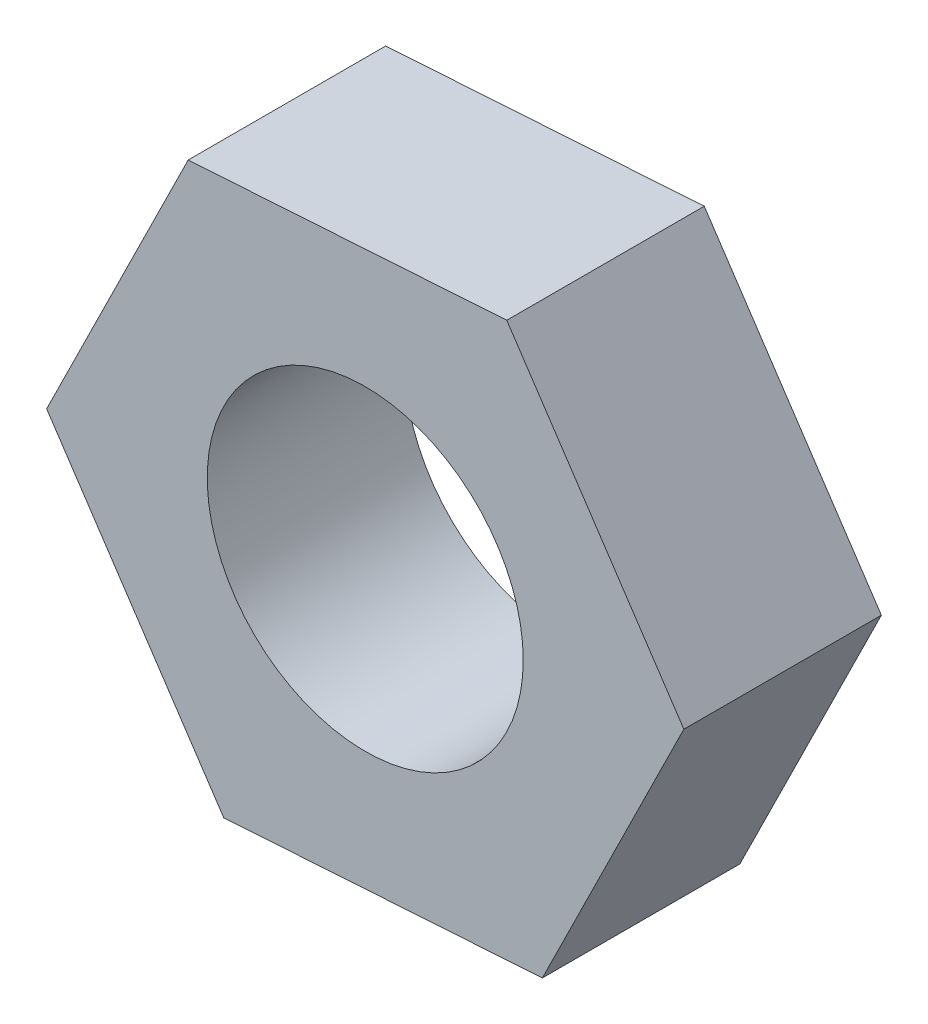
SolidWorks part; units mm, degrees
material "AISI 304"
ref_plane "Front Plane" through (0, 0, 0) normal (0, 0, 1) x (1, 0, 0)
ref_plane "Top Plane" through (0, 0, 0) normal (0, 1, 0) x (1, 0, 0)
ref_plane "Right Plane" through (0, 0, 0) normal (1, 0, 0) x (0, 0, -1)
sketch "Sketch1" plane through (0, 0, 0) normal (0, 0, 1) x (1, 0, 0)
  line L1 (4.4836, -6.7254) -> (8.0661, 0.5202)
  line L2 (8.0661, 0.5202) -> (3.5826, 7.2456)
  line L3 (3.5826, 7.2456) -> (-4.4836, 6.7254)
  line L4 (-4.4836, 6.7254) -> (-8.0661, -0.5202)
  line L5 (-8.0661, -0.5202) -> (-3.5826, -7.2456)
  line L6 (-3.5826, -7.2456) -> (4.4836, -6.7254)
  circle A0 centre (0, 0) radius 4
  circle A1 centre (0, 0) radius 7 construction
  dimension "D1" = 8
  dimension "D2" = 14
extrude "Boss-Extrude1" add sketch "Sketch1" along normal mid plane 5
